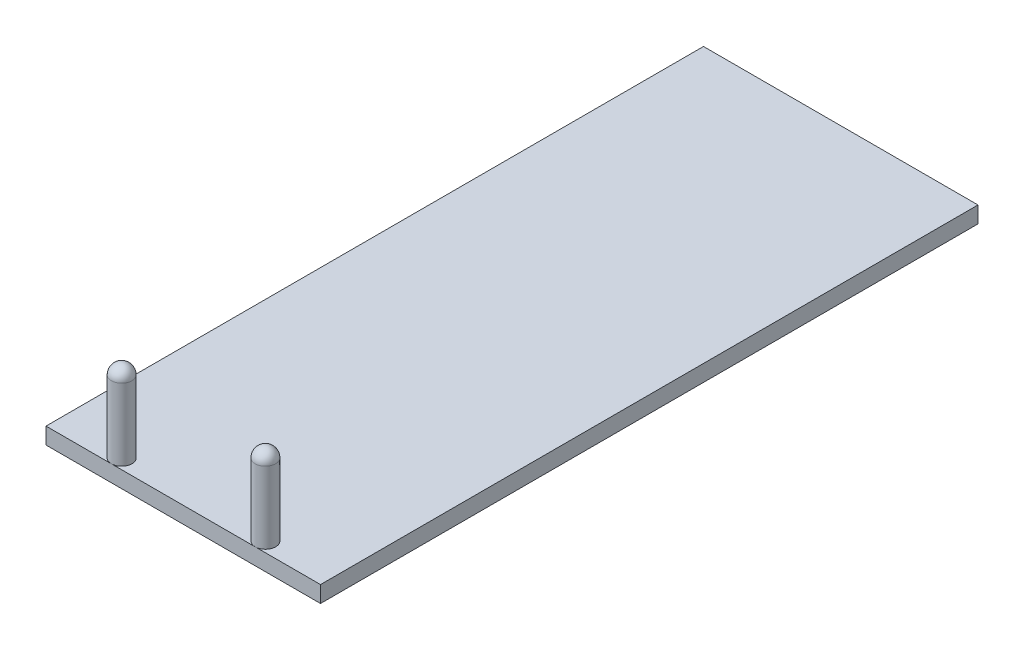
SolidWorks part; units mm, degrees
ref_plane "Спереди" through (0, 0, 0) normal (0, 0, 1) x (1, 0, 0)
ref_plane "Сверху" through (0, 0, 0) normal (0, 1, 0) x (1, 0, 0)
ref_plane "Справа" through (0, 0, 0) normal (1, 0, 0) x (0, 0, -1)
other "Configuration Table"
sketch "Эскиз1" plane through (0, 0, 0) normal (0, 1, 0) x (1, 0, 0)
  line L0 (-423.8908, 0) -> (423.8908, 0) construction
  line L1 (-167, 400) -> (167, 400)
  line L2 (-167, 400) -> (-167, -400)
  line L3 (-167, -400) -> (167, -400)
  line L4 (167, 400) -> (167, -400)
  line L5 (0, 366.5529) -> (0, -366.5529) construction
  point P8 (-167, 0)
  point P9 (0, 400)
  dimension "D1" = 800
  dimension "D2" = 334
extrude "Бобышка-Вытянуть1" add sketch "Эскиз1" against normal blind 20
sketch "Эскиз3" plane through (0, 0, 0) normal (0, 1, 0) x (1, 0, 0)
  line L0 (0, 233.3084) -> (0, -490.6965) construction
  line L1 (186.2282, 3.3822) -> (-153.8699, -482.3282) construction
  line L2 (0, -262.5793) -> (87.4704, -387.5) construction
  line L4 (-167, -400) -> (167, -400) construction
  circle A0 centre (0, -262.5793) radius 140 construction
  circle A1 centre (-87.4704, -387.5) radius 12.5
  circle A2 centre (87.4704, -387.5) radius 12.5
  point P9 (0, 0)
  point P10 (0, 0)
  point P11 (0, -53.8667)
  point P14 (0, -262.5793)
  point P15 (0, -490.6965)
  dimension "D1" = 280
  dimension "D3" = 25
  dimension "D6" = 25
  dimension "D2" = 35
  dimension "D5" = 35
  dimension "D4" = 2
extrude "Бобышка-Вытянуть4" add sketch "Эскиз3" along normal blind 100
fillet "Скругление1" radius 12.5 2 edges at (87.4704, 100, 400) (-87.4704, 100, 400)
